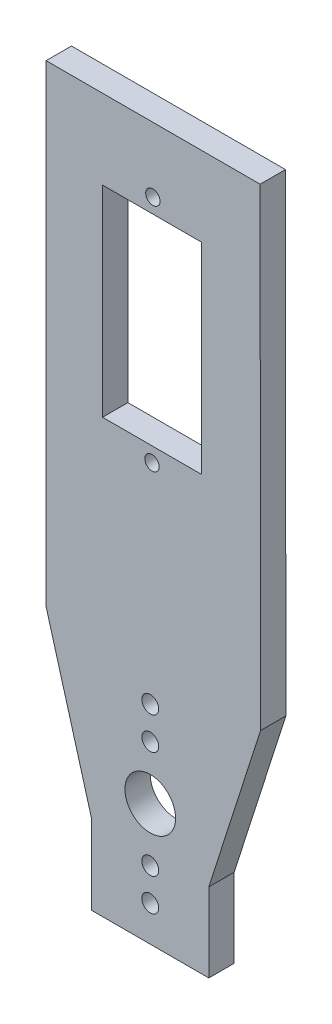
SolidWorks part; units mm, degrees
ref_plane "Front Plane" through (0, 0, 0) normal (0, 0, 1) x (1, 0, 0)
ref_plane "Top Plane" through (0, 0, 0) normal (0, 1, 0) x (1, 0, 0)
ref_plane "Right Plane" through (0, 0, 0) normal (1, 0, 0) x (0, 0, -1)
sketch "Model" plane through (0, 0, 0) normal (0, 0, 1) x (1, 0, 0)
  line L306 (-369.2066, 212.9265) -> (-369.2066, 257.1649)
  line L307 (-369.2066, 257.1649) -> (-343.8065, 257.1649)
  line L310 (-362.0525, 173.4925) -> (-369.2066, 212.9265)
  line L311 (-351.6601, 173.4925) -> (-343.8064, 213.5615)
  line L330 (-343.8064, 213.5615) -> (-343.8064, 257.1649)
  line L360 (-356.8563, 172.4499) -> (-356.5017, 172.178)
  line L361 (-356.5017, 172.178) -> (-356.0683, 172.2806)
  line L362 (-356.0683, 172.2806) -> (-355.8538, 171.8865)
  line L363 (-355.8538, 171.8865) -> (-355.4166, 171.8023)
  line L364 (-355.4166, 171.8023) -> (-355.3793, 171.3541)
  line L365 (-355.3793, 171.3541) -> (-355.0138, 171.0974)
  line L366 (-355.0138, 171.0974) -> (-355.1601, 170.6727)
  line L367 (-355.1601, 170.6727) -> (-354.9295, 170.288)
  line L368 (-354.9295, 170.288) -> (-355.2342, 169.96)
  line L369 (-355.2342, 169.96) -> (-355.1785, 169.5139)
  line L370 (-355.1785, 169.5139) -> (-355.5888, 169.3396)
  line L371 (-355.5888, 169.3396) -> (-355.7176, 168.909)
  line L372 (-355.7176, 168.909) -> (-356.1626, 168.9184)
  line L373 (-356.1626, 168.9184) -> (-356.4535, 168.578)
  line L374 (-356.4535, 168.578) -> (-356.8563, 168.7694)
  line L375 (-356.8563, 168.7694) -> (-357.2591, 168.578)
  line L376 (-357.2591, 168.578) -> (-357.55, 168.9184)
  line L377 (-357.55, 168.9184) -> (-357.995, 168.909)
  line L378 (-357.995, 168.909) -> (-358.1238, 169.3396)
  line L379 (-358.1238, 169.3396) -> (-358.5341, 169.5139)
  line L380 (-358.5341, 169.5139) -> (-358.4784, 169.96)
  line L381 (-358.4784, 169.96) -> (-358.7831, 170.288)
  line L382 (-358.7831, 170.288) -> (-358.5525, 170.6727)
  line L383 (-358.5525, 170.6727) -> (-358.6988, 171.0974)
  line L384 (-358.6988, 171.0974) -> (-358.3333, 171.3541)
  line L385 (-358.3333, 171.3541) -> (-358.296, 171.8023)
  line L386 (-358.296, 171.8023) -> (-357.8588, 171.8865)
  line L387 (-357.8588, 171.8865) -> (-357.6443, 172.2806)
  line L388 (-357.6443, 172.2806) -> (-357.2109, 172.178)
  line L389 (-357.2109, 172.178) -> (-356.8563, 172.4499)
  line L462 (-362.888, 248.8622) -> (-351.1786, 248.8622)
  line L463 (-351.1786, 248.8622) -> (-351.1786, 225.0624)
  line L464 (-351.1786, 225.0624) -> (-362.888, 225.0624)
  line L465 (-362.888, 225.0624) -> (-362.888, 248.8622)
  circle A0 centre (-357.0333, 223.3243) radius 0.9525
  spline S348 degree 3 poles (-362.0525, 173.4925) (-362.5791, 172.5803) (-362.8563, 171.5457) (-362.8563, 170.4925) knots 0 0 0 0 0.2 0.2 0.2 0.2
  spline S349 degree 3 poles (-362.8563, 170.4925) (-362.8563, 167.1788) (-360.1701, 164.4926) (-356.8563, 164.4926) knots 0.2 0.2 0.2 0.2 0.4 0.4 0.4 0.4
  spline S350 degree 3 poles (-356.8563, 164.4926) (-353.5425, 164.4926) (-350.8563, 167.1788) (-350.8563, 170.4925) knots 0.4 0.4 0.4 0.4 0.6 0.6 0.6 0.6
  spline S351 degree 3 poles (-350.8563, 170.4925) (-350.8563, 171.5457) (-351.1335, 172.5803) (-351.6601, 173.4925) knots 0.6 0.6 0.6 0.6 1 1 1 1
  spline S474 degree 3 poles (-357.9858, 223.3243) (-357.9858, 222.7982) (-357.5594, 222.3718) (-357.0333, 222.3718) knots 0 0 0 0 0.2 0.2 0.2 0.2
  spline S475 degree 3 poles (-357.0333, 222.3718) (-356.5072, 222.3718) (-356.0808, 222.7982) (-356.0808, 223.3243) knots 0.2 0.2 0.2 0.2 0.4 0.4 0.4 0.4
  spline S476 degree 3 poles (-356.0808, 223.3243) (-356.0808, 223.8504) (-356.5072, 224.2768) (-357.0333, 224.2768) knots 0.4 0.4 0.4 0.4 0.6 0.6 0.6 0.6
  spline S477 degree 3 poles (-357.0333, 224.2768) (-357.5594, 224.2768) (-357.9858, 223.8504) (-357.9858, 223.3243) knots 0.6 0.6 0.6 0.6 1 1 1 1
  spline S478 degree 3 poles (-357.9858, 250.6003) (-357.9858, 250.0742) (-357.5594, 249.6478) (-357.0333, 249.6478) knots 0 0 0 0 0.2 0.2 0.2 0.2
  spline S479 degree 3 poles (-357.0333, 249.6478) (-356.5072, 249.6478) (-356.0808, 250.0742) (-356.0808, 250.6003) knots 0.2 0.2 0.2 0.2 0.4 0.4 0.4 0.4
  spline S480 degree 3 poles (-356.0808, 250.6003) (-356.0808, 251.1264) (-356.5072, 251.5528) (-357.0333, 251.5528) knots 0.4 0.4 0.4 0.4 0.6 0.6 0.6 0.6
  spline S481 degree 3 poles (-357.0333, 251.5528) (-357.5594, 251.5528) (-357.9858, 251.1264) (-357.9858, 250.6003) knots 0.6 0.6 0.6 0.6 1 1 1 1
  dimension "D1" = 1.905
  dimension "D2" = 23.7998
  dimension "D3" = 11.7094
  dimension "D4" = 1.7381
  dimension "D5" = 92.6723
  dimension "D6" = 25.4002
sketch "Sketch1" plane through (0, 0, 0) normal (0, 0, 1) x (1, 0, 0)
  line L0 (-363.7846, 176.4925) -> (-369.1806, 195.5762)
  line L1 (-369.1806, 195.5762) -> (-369.1806, 251.556)
  line L2 (-369.1806, 251.556) -> (-343.8537, 251.556)
  line L3 (-343.8537, 251.556) -> (-343.8065, 195.5762)
  line L4 (-343.8065, 195.5762) -> (-349.928, 176.4925)
  line L5 (-362.8563, 170.4925) -> (-350.8563, 170.4925) construction
  line L6 (-362.5012, 242.1422) -> (-350.7918, 242.1422)
  line L7 (-362.5012, 242.1422) -> (-362.5012, 218.3424)
  line L8 (-362.5012, 218.3424) -> (-350.7918, 218.3424)
  line L9 (-350.7918, 242.1422) -> (-350.7918, 218.3424)
  line L10 (-356.8563, 164.4926) -> (-356.8563, 181.556) construction
  line L11 (-356.8563, 164.4926) -> (-356.5171, 251.556) construction
  line L14 (-363.7846, 176.4925) -> (-363.7846, 167.1539)
  line L15 (-363.7846, 167.1539) -> (-349.928, 167.1539)
  line L16 (-349.928, 176.4925) -> (-349.928, 167.1539)
  circle A1 centre (-356.6533, 216.6043) radius 0.85
  circle A2 centre (-356.547, 243.8803) radius 0.85
  circle A3 centre (-356.8563, 181.556) radius 3
  point P3 (-356.6465, 242.1422)
  point P6 (-356.6465, 218.3424)
  dimension "D3" = 1.7
  dimension "D6" = 1.7
  dimension "D11" = 6
  dimension "D1" = 23.7998
  dimension "D2" = 11.7094
  dimension "D4" = 1.7381
  dimension "D5" = 1.7381
  dimension "D9" = 25.3268
extrude "Boss-Extrude3" add sketch "Sketch1" along normal blind 3
sketch "Sketch2" plane through (0, 0, 3) normal (0, 0, 1) x (1, 0, 0)
  circle A0 centre (-356.8563, 171.356) radius 1.0009
  circle A1 centre (-356.8563, 175.206) radius 1.0009
  circle A2 centre (-356.8563, 187.906) radius 1.0009
  circle A3 centre (-356.8563, 191.756) radius 1.0009
  dimension "D1" = 2.0018
  dimension "D2" = 2.0018
  dimension "D3" = 2.0018
  dimension "D4" = 2.0018
extrude "Cut-Extrude1" cut sketch "Sketch2" against normal through all
equation "\"selftap\"=2.0018"
equation "\"D4@Sketch2\"=\"selftap\""
equation "\"D3@Sketch2\"=\"selftap\""
equation "\"D2@Sketch2\"=\"selftap\""
equation "\"D1@Sketch2\"=\"selftap\""
